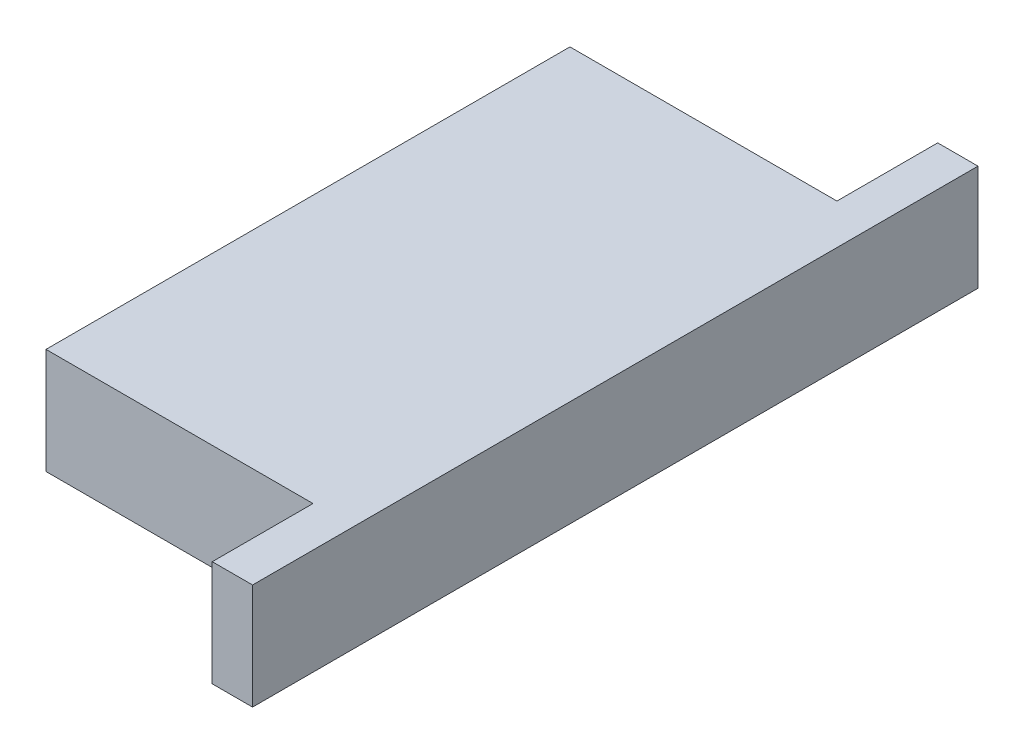
SolidWorks part; units mm, degrees
ref_plane "Front Plane" through (0, 0, 0) normal (0, 0, 1) x (1, 0, 0)
ref_plane "Top Plane" through (0, 0, 0) normal (0, 1, 0) x (1, 0, 0)
ref_plane "Right Plane" through (0, 0, 0) normal (1, 0, 0) x (0, 0, -1)
sketch "Sketch1" plane through (0, 0, 0) normal (0, 1, 0) x (1, 0, 0)
  line L0 (15.25, 36) -> (15.25, -36)
  line L1 (11.25, 26) -> (-15.25, 26)
  line L2 (15.25, 26) -> (15.25, -26)
  line L3 (11.25, -26) -> (-15.25, -26)
  line L4 (-15.25, 26) -> (-15.25, -26)
  line L5 (15.25, 26) -> (-15.25, -26) construction
  line L6 (15.25, -26) -> (-15.25, 26) construction
  line L7 (15.25, 36) -> (11.25, 36)
  line L8 (11.25, 36) -> (11.25, 26)
  line L9 (15.25, -36) -> (11.25, -36)
  line L10 (11.25, -36) -> (11.25, -26)
  point P0 (0, 0)
  point P9 (15.25, 0)
  dimension "D1" = 52
  dimension "D2" = 30.5
  dimension "D3" = 72
  dimension "D4" = 4
extrude "Boss-Extrude1" add sketch "Sketch1" along normal blind 10.5 contours L3 L4 L1 L8 L7 L0 L9 L10
